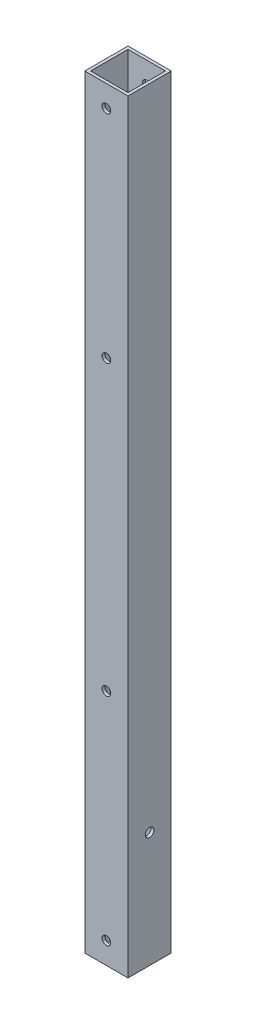
SolidWorks part; units mm, degrees
material "6061 合金"
ref_plane "前视基准面" through (0, 0, 0) normal (0, 0, 1) x (1, 0, 0)
ref_plane "上视基准面" through (0, 0, 0) normal (0, 1, 0) x (1, 0, 0)
ref_plane "右视基准面" through (0, 0, 0) normal (1, 0, 0) x (0, 0, -1)
sketch "草图1" plane through (0, 0, 0) normal (0, 1, 0) x (1, 0, 0)
  line L0 (-6.5, -6.5) -> (-6.5, 6.5)
  line L1 (-7.5, -7.5) -> (7.5, -7.5)
  line L2 (-7.5, -7.5) -> (-7.5, 7.5)
  line L3 (-7.5, 7.5) -> (7.5, 7.5)
  line L4 (7.5, -7.5) -> (7.5, 7.5)
  line L5 (-7.5, -7.5) -> (7.5, 7.5) construction
  line L6 (-7.5, 7.5) -> (7.5, -7.5) construction
  line L7 (-6.5, 6.5) -> (6.5, 6.5)
  line L8 (6.5, -6.5) -> (6.5, 6.5)
  line L9 (-6.5, -6.5) -> (6.5, -6.5)
  point P0 (0, 0)
  dimension "D1" = 15
  dimension "D2" = 1
extrude "凸台-拉伸1" add sketch "草图1" along normal blind 265
sketch "草图2" plane through (0, 0, 7.5) normal (0, 0, 1) x (1, 0, 0)
  line L0 (0, 265) -> (0, 0) construction
  line L1 (-7.5, 265) -> (7.5, 265) construction
  line L2 (-7.5, 132.5) -> (7.5, 132.5) construction
  line L3 (-7.5, 265) -> (-7.5, 0) construction
  line L4 (7.5, 265) -> (7.5, 0) construction
  circle A0 centre (0, 7.5) radius 1.5
  circle A1 centre (0, 257.5) radius 1.5
  circle A2 centre (0, 182.5) radius 1.5
  circle A3 centre (0, 82.5) radius 1.5
  dimension "D1" = 3
  dimension "D2" = 250
  dimension "D3" = 100
extrude "切除-拉伸1" cut sketch "草图2" against normal through all
sketch "草图3" plane through (7.5, 0, 0) normal (1, 0, 0) x (0, 0, -1)
  line L0 (0, 265) -> (0, 0) construction
  line L1 (-7.5, 265) -> (7.5, 265) construction
  circle A0 centre (0, 40) radius 1.5
  dimension "D1" = 3
  dimension "D2" = 40
extrude "切除-拉伸2" cut sketch "草图3" against normal through all
